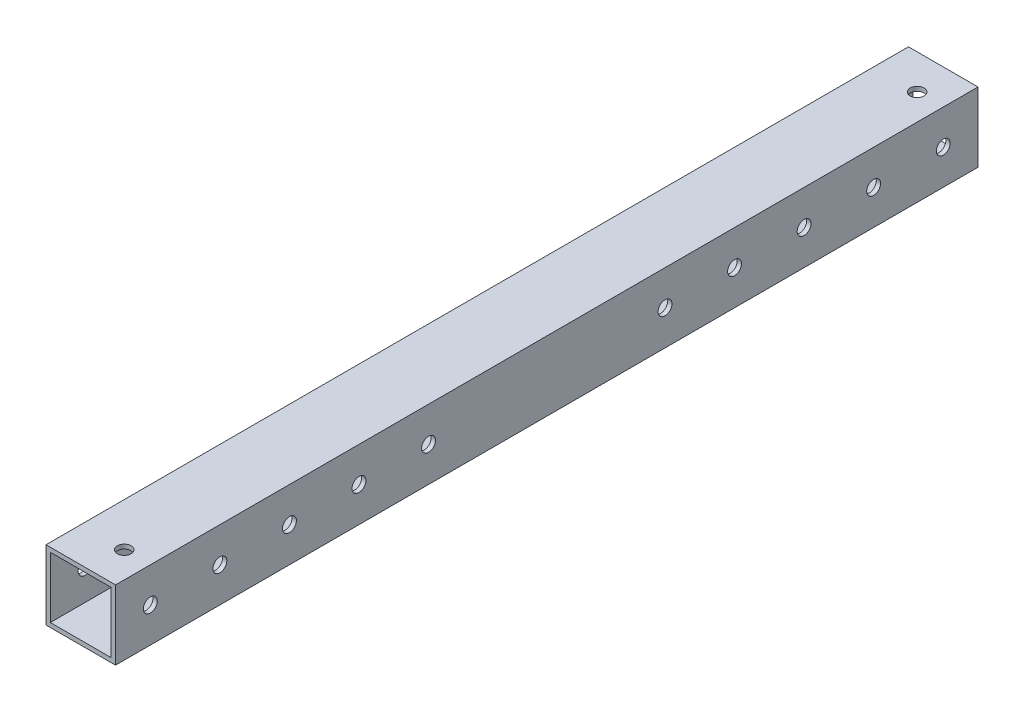
SolidWorks part; units mm, degrees
ref_plane "Front Plane" through (0, 0, 0) normal (0, 0, 1) x (1, 0, 0)
ref_plane "Top Plane" through (0, 0, 0) normal (0, 1, 0) x (1, 0, 0)
ref_plane "Right Plane" through (0, 0, 0) normal (1, 0, 0) x (0, 0, -1)
sketch "Sketch1" plane through (0, 0, 0) normal (0, 0, 1) x (1, 0, 0)
  line L1 (0, 0) -> (25.4, 0)
  line L2 (0, 0) -> (0, 25.4)
  line L3 (0, 25.4) -> (25.4, 25.4)
  line L4 (25.4, 0) -> (25.4, 25.4)
  line L5 (1.5875, 1.5875) -> (23.8125, 1.5875)
  line L6 (1.5875, 1.5875) -> (1.5875, 23.8125)
  line L7 (1.5875, 23.8125) -> (23.8125, 23.8125)
  line L8 (23.8125, 1.5875) -> (23.8125, 23.8125)
  dimension "D1" = 25.4
  dimension "D2" = 1.5875
  dimension "D3" = 1.5875
  dimension "D4" = 1.5875
  dimension "D5" = 1.5875
extrude "Boss-Extrude1" add sketch "Sketch1" along normal blind 314.96
sketch "Sketch3" plane through (0, 25.4, 0) normal (0, 1, 0) x (1, 0, 0)
  line L0 (0, -314.96) -> (0, 0) construction
  line L1 (25.4, -314.96) -> (0, -314.96) construction
  line L2 (25.4, 0) -> (0, 0) construction
  circle A0 centre (15.875, -302.26) radius 2.54
  circle A1 centre (15.875, -12.7) radius 2.54
  dimension "D3" = 5.08
  dimension "D1" = 15.875
  dimension "D2" = 12.7
  dimension "D4" = 12.7
extrude "Cut-Extrude2" cut sketch "Sketch3" against normal through all
sketch "Sketch4" plane through (25.4, 0, 0) normal (1, 0, 0) x (0, 0, -1)
  line L0 (-314.96, 25.4) -> (0, 25.4) construction
  line L1 (-314.96, 0) -> (-314.96, 25.4) construction
  line L3 (-157.48, 25.4) -> (-157.48, 0) construction
  line L4 (-314.96, 0) -> (0, 0) construction
  circle A0 centre (-302.26, 12.7) radius 2.54
  circle A2 centre (-276.86, 12.7) radius 2.54
  circle A3 centre (-251.46, 12.7) radius 2.54
  circle A4 centre (-226.06, 12.7) radius 2.54
  circle A5 centre (-200.66, 12.7) radius 2.54
  circle A6 centre (-114.3, 12.7) radius 2.54
  circle A7 centre (-88.9, 12.7) radius 2.54
  circle A8 centre (-63.5, 12.7) radius 2.54
  circle A9 centre (-38.1, 12.7) radius 2.54
  circle A10 centre (-12.7, 12.7) radius 2.54
  dimension "D1" = 5.08
  dimension "D2" = 12.7
  dimension "D3" = 12.7
  dimension "D4" = 5
extrude "Cut-Extrude3" cut sketch "Sketch4" against normal through all
